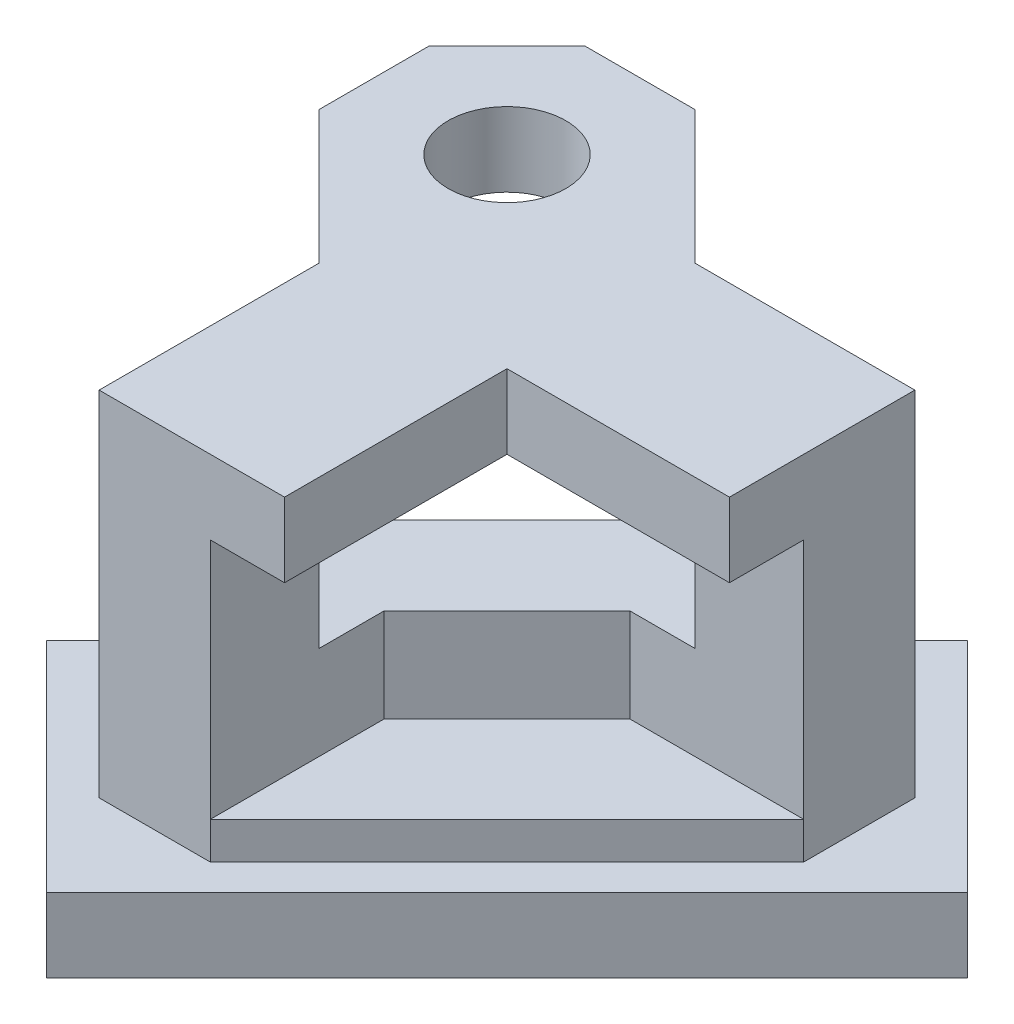
SolidWorks part; units mm, degrees
ref_plane "Front Plane" through (0, 0, 0) normal (0, 0, 1) x (1, 0, 0)
ref_plane "Top Plane" through (0, 0, 0) normal (0, 1, 0) x (1, 0, 0)
ref_plane "Right Plane" through (0, 0, 0) normal (1, 0, 0) x (0, 0, -1)
sketch "Sketch1" plane through (0, 0, 0) normal (0, 1, 0) x (1, 0, 0)
  line L0 (-11, -11) -> (11, 11) construction
  line L1 (-11, 11) -> (11, 11) construction
  line L2 (-11, 11) -> (-11, -11) construction
  line L3 (-11, -11) -> (11, -11) construction
  line L4 (11, 11) -> (11, -11) construction
  line L5 (-11, -11) -> (-1, -11)
  line L6 (-1, -11) -> (-1, 1)
  line L8 (-1, 1) -> (11, 1)
  line L9 (11, 1) -> (11, 11)
  line L10 (-5, -11) -> (-5, 5) construction
  line L11 (-5, 5) -> (11, 5) construction
  line L12 (-8.7549, 8.7549) -> (-5.9265, 5.9265) construction
  line L13 (-8.7549, 8.7549) -> (-11, 11) construction
  line L14 (-13.972, 18.175) -> (-18.175, 13.972)
  line L15 (-18.175, 13.972) -> (-18.175, 8.028)
  line L16 (-18.175, 8.028) -> (-11, 0.853)
  line L17 (-13.972, 18.175) -> (-8.028, 18.175)
  line L18 (-8.028, 18.175) -> (-0.853, 11)
  line L19 (-11, 11) -> (-13.2451, 13.2451) construction
  line L20 (-13.2451, 13.2451) -> (-16.0735, 16.0735) construction
  line L21 (-14.175, 11) -> (-18.175, 11) construction
  line L22 (-11, 0.853) -> (-5, -5.147) construction
  line L23 (-0.853, 11) -> (5.147, 5) construction
  line L24 (-11, 0.853) -> (-11, -11)
  line L25 (-0.853, 11) -> (11, 11)
  line L26 (-11, 0.853) -> (-0.853, 11) construction
  circle A0 centre (-11, 11) radius 3.175
  point P4 (0, 0)
  point P26 (-16.0735, 16.0735)
  dimension "D3" = 6.35
  dimension "D2" = 22
  dimension "D1" = 10
  dimension "D4" = 6
  dimension "D6" = 4
  dimension "D7" = 4
  dimension "D5" = 4
extrude "Boss-Extrude1" add sketch "Sketch1" against normal blind 4 contours A0 | L5 L6 L8 L9 L25 L18 L17 L14 L15 L16 L24
sketch "Sketch2" plane through (0, -4, 0) normal (0, -1, 0) x (1, 0, 0)
  line L0 (-0.853, -11) -> (11, -11) construction
  line L1 (-0.853, -11) -> (5.147, -5) construction
  line L2 (-11, -0.853) -> (-11, 11) construction
  line L3 (-11, -0.853) -> (-5, 5.147) construction
  line L4 (-0.853, -11) -> (11, -11)
  line L5 (-0.853, -11) -> (5.147, -5)
  line L6 (-11, -0.853) -> (-11, 11)
  line L7 (-11, -0.853) -> (-5, 5.147)
  line L8 (-5, 5.147) -> (-5, 11)
  line L9 (-5, 11) -> (-11, 11)
  line L10 (5.147, -5) -> (11, -5)
  line L11 (11, -5) -> (11, -11)
extrude "Boss-Extrude2" add sketch "Sketch2" along normal blind 8
sketch "Sketch3" plane through (0, -12, 0) normal (0, -1, 0) x (1, 0, 0)
  line L0 (5.147, -5) -> (-0.853, -11) construction
  line L1 (-0.853, -11) -> (11, -11) construction
  line L2 (11, -11) -> (11, -5) construction
  line L3 (11, -5) -> (5.147, -5) construction
  line L4 (-5, 11) -> (-11, 11) construction
  line L5 (-11, 11) -> (-11, -0.853) construction
  line L6 (-11, -0.853) -> (-5, 5.147) construction
  line L7 (-5, 5.147) -> (-5, 11) construction
  line L8 (5.147, -5) -> (-0.853, -11) construction
  line L9 (-0.853, -11) -> (11, -11)
  line L10 (11, -11) -> (11, -5)
  line L11 (11, -5) -> (5.147, -5)
  line L12 (-5, 11) -> (-11, 11)
  line L13 (-11, 11) -> (-11, -0.853)
  line L14 (-11, -0.853) -> (-5, 5.147) construction
  line L15 (-5, 5.147) -> (-5, 11)
  line L16 (-11, -0.853) -> (-0.853, -11)
  line L17 (-5, 5.147) -> (-5, 1.6323)
  line L18 (-5, 1.6323) -> (1.6323, -5)
  line L19 (1.6323, -5) -> (5.147, -5)
  dimension "D1" = 6
extrude "Boss-Extrude3" add sketch "Sketch3" along normal blind 5.05
sketch "Sketch4" plane through (0, -17.05, 0) normal (0, -1, 0) x (1, 0, 0)
  line L0 (-5, 11) -> (-11, 11) construction
  line L1 (11, -11) -> (11, -5) construction
  line L2 (-0.853, -11) -> (11, -11) construction
  line L3 (-11, -0.853) -> (-0.853, -11) construction
  line L4 (-11, 11) -> (-11, -0.853) construction
  line L5 (-5, 11) -> (-11, 11)
  line L6 (11, -11) -> (11, -5)
  line L7 (-0.853, -11) -> (11, -11)
  line L8 (-11, -0.853) -> (-0.853, -11)
  line L9 (-11, 11) -> (-11, -0.853)
  line L10 (-5, 11) -> (11, -5)
extrude "Boss-Extrude4" add sketch "Sketch4" along normal blind 2
sketch "Sketch5" plane through (0, -19.05, 0) normal (0, -1, 0) x (1, 0, 0)
  line L0 (-19.7549, 5.0735) -> (5.0735, -19.7549)
  line L1 (5.0735, -19.7549) -> (16.8284, -8)
  line L2 (16.8284, -8) -> (-8, 16.8284)
  line L3 (-8, 16.8284) -> (-19.7549, 5.0735)
  line L4 (11, -5) -> (-5, 11) construction
  line L5 (-5.9265, -5.9265) -> (-7.3407, -7.3407) construction
  line L6 (-11, -0.853) -> (-0.853, -11) construction
  line L7 (-11, 11) -> (-12.4142, 12.4142) construction
  line L8 (3, 3) -> (4.4142, 4.4142) construction
  dimension "D1" = 2
extrude "Boss-Extrude5" add sketch "Sketch5" along normal blind 4
equation "\"w\"= 16'wall width"
equation "\"t\"= 6'wall thickness"
equation "\"D2@Sketch1\"=\"w\"+\"t\""
equation "\"offset\"= 0.75in'baseplate's top surface to sample's top surface"
equation "\"h_top\"= 4"
equation "\"D1@Boss-Extrude1\"=\"h_top\""
equation "\"lip\"= 4'clamp overhang"
equation "\"h_base\"= 4'height of base"
equation "\"D1@Sketch1\"=\"lip\"+\"t\""
equation "\"D4@Sketch1\"=\"t\""
equation "\"chamfer\"= .025"
equation "\"screw_diam\"= .25in"
equation "\"D3@Sketch1\"= \"screw_diam\""
equation "\"screw_offset\"= 4"
equation "\"D6@Sketch1\"=\"screw_offset\""
equation "\"D7@Sketch1\"=\"screw_offset\""
equation "\"screw_clearance\"= 4"
equation "\"slot_height\"= 8"
equation "\"D1@Boss-Extrude2\"=\"slot_height\""
equation "\"D1@Sketch3\"=\"t\""
equation "\"D1@Boss-Extrude3\"=\"offset\"-\"slot_height\"-\"h_base\"-\"h_base_platform\""
equation "\"h_base_platform\"= 2"
equation "\"D1@Boss-Extrude4\"=\"h_base_platform\""
equation "\"t_base\"= 2"
equation "\"D1@Sketch5\"=\"t_base\""
equation "\"D1@Boss-Extrude5\"=\"h_base\""
equation "\"D5@Sketch1\"=\"screw_clearance\""
